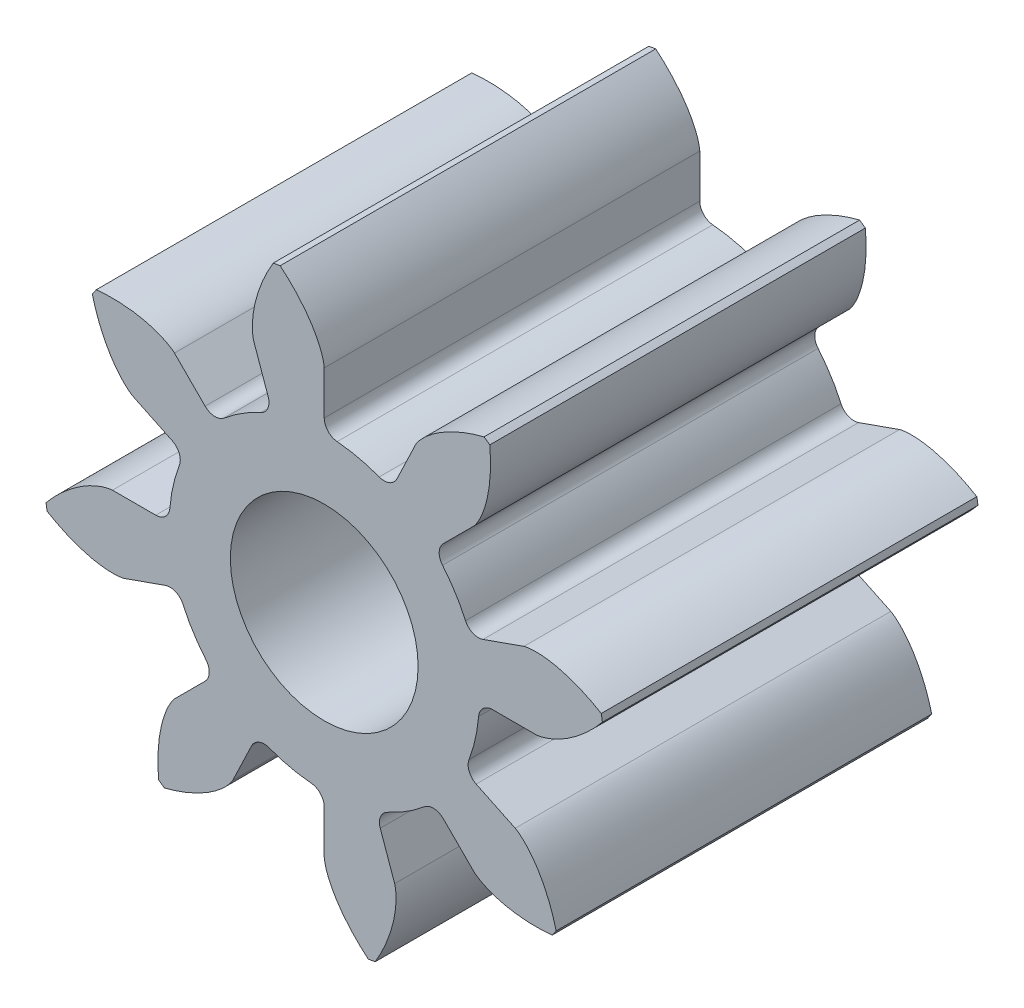
SolidWorks part; units mm, degrees
material "Laiton"
ref_plane "Front Plane" through (0, 0, 0) normal (0, 0, 1) x (1, 0, 0)
ref_plane "Top Plane" through (0, 0, 0) normal (0, 1, 0) x (1, 0, 0)
ref_plane "Right Plane" through (0, 0, 0) normal (1, 0, 0) x (0, 0, -1)
sketch "Sketch1" plane through (0, 0, 0) normal (0, 0, 1) x (1, 0, 0)
  line L0 (1.1276, 0) -> (0.825, 0)
  line L1 (1.4785, 0.2532) -> (-1.4785, -0.2532)
  line L2 (0, 0) -> (1.1999, 0.0179) construction
  circle A0 centre (0, 0) radius 1.1276 construction
  circle A1 centre (0, 0) radius 1.5
  circle A2 centre (0, 0) radius 0.825
  circle A3 centre (0, 0) radius 1.2 construction
  spline S0 degree 4 poles (1.1276, 0) (1.1285, 0) (1.1308, 0.0001) (1.1352, 0.0005) (1.1424, 0.0015) (1.1514, 0.0032) (1.1631, 0.0059) (1.1767, 0.0097) (1.1914, 0.0146) (1.2073, 0.0206) (1.2229, 0.0273) (1.2383, 0.0345) (1.2534, 0.0422) (1.2714, 0.0521) (1.2927, 0.0649) (1.3171, 0.0809) (1.3439, 0.1005) (1.3705, 0.1219) (1.3959, 0.1441) (1.4206, 0.1679) (1.444, 0.1917) (1.4673, 0.2177) (1.4883, 0.2424) (1.5106, 0.2713) (1.5284, 0.295) (1.5505, 0.3276) (1.5632, 0.3473) (1.5775, 0.3707) (1.5837, 0.3813) (1.5875, 0.3879) knots 0 0 0 0 0 0.005377 0.015084 0.028532 0.04661 0.064855 0.092111 0.119476 0.146842 0.174209 0.201575 0.228941 0.256307 0.307035 0.361767 0.4165 0.471232 0.525964 0.580697 0.635429 0.690161 0.744894 0.799626 0.854358 0.909091 0.954545 1 1 1 1 1 construction
  spline S1 degree 4 poles (1.1276, 0) (1.1285, 0) (1.1308, 0.0001) (1.1352, 0.0005) (1.1424, 0.0015) (1.1514, 0.0032) (1.1631, 0.0059) (1.1767, 0.0097) (1.1914, 0.0146) (1.2073, 0.0206) (1.2229, 0.0273) (1.2383, 0.0345) (1.2534, 0.0422) (1.2714, 0.0521) (1.2927, 0.0649) (1.3171, 0.0809) (1.3439, 0.1005) (1.3705, 0.1219) (1.3959, 0.1441) (1.4206, 0.1679) (1.444, 0.1917) (1.4673, 0.2177) (1.4883, 0.2424) (1.5106, 0.2713) (1.5284, 0.295) (1.5457, 0.3205) (1.554, 0.3331) (1.5581, 0.3396) knots 0 0 0 0 0 0.005377 0.015084 0.028532 0.04661 0.064855 0.092111 0.119476 0.146842 0.174209 0.201575 0.228941 0.256307 0.307035 0.361767 0.4165 0.471232 0.525964 0.580697 0.635429 0.690161 0.744894 0.799626 0.854358 0.909091 0.909091 0.909091 0.909091 0.909091
  dimension "D1" = 2.2553
  dimension "D2" = 3
  dimension "D3" = 1.65
  dimension "D5" = 2.4
  dimension "D4" = 8.863
extrude "Boss-Extrude3" add sketch "Sketch1" along normal blind 2 contours L1 A2 | A2 L1 | L0 S1 A1 L1 A2
mirror "Mirror2" about plane through (0, 0, 2) normal (0.1688, -0.9857, 0) of "Boss-Extrude3"
fillet "Fillet1" radius 0.075 2 edges at (0.778, 0.2745, 1) (0.825, 0, 1)
pattern_circular "CirPattern8" count 8 over 360 about axis through (0, 0, 2) along (0, 0, -1) of "Boss-Extrude3", "Mirror2", "Fillet1"
sketch "Sketch3" plane through (0, 0, 2) normal (0, 0, 1) x (1, 0, 0)
  circle A0 centre (0, 0) radius 0.5
  dimension "D1" = 1
extrude "Cut-Extrude2" cut sketch "Sketch3" against normal through all
equation "\"d\"= \"m\" * \"N\"'Pitch diameter"
equation "\"N\"= 8'Number of teeth"
equation "\"bl\"= 0.1mm'Backlash"
equation "\"pa\"= 20deg'Pressure angle (deg)"
equation "\"pc\"= ( 3.1415 * \"d\" ) / \"N\"\t'Circular pitch"
equation "\"m\"= 0.3'module"
equation "\"P\"= \"N\" / \"d\"\t\t\t'Diametral pitch"
equation "\"a\"= 1/\"P\"\t\t\t'Addendum distance"
equation "\"b\"= 1.25 / \"P\"'Dedendum distance"
equation "\"rb\"= (\"d\"/2)*cos(\"pa\")\t\t'base circle radius"
equation "\"cp\"= 3.1415/\"P\"\t\t'Circular pitch"
equation "\"t\"= ( \"cp\" / 2 ) - \"bl\"'tooth tickness"
equation "\"c\"=\"b\"-\"a\"\t\t\t'Clearance"
equation "\"facewidth\"= 2mm'face width"
equation "\"rbd\"= \"rb\" * 2'base circle diameter"
equation "\"D1@Sketch1\"=\"rbd\""
equation "\"D2@Sketch1\"= \"d\" + (\"a\" * 2)"
equation "\"D3@Sketch1\" = \"ded\""
equation "\"D4@Sketch1\"= ((\"t\" /2) / (\"d\"/2)) * (180/3.1415)"
equation "\"D1@Boss-Extrude3\"=\"facewidth\""
equation "\"D1@Fillet1\"=\"c\""
equation "\"D1@CirPattern8\"=\"N\""
equation "\"D5@Sketch1\"=\"d\""
equation "\"ded1\"= \"d\" - 2 * ( ( ( \"d\" / 2 ) - \"rb\" ) + ( 0.5 * ( 1.25 / \"P\" ) ) )"
equation "\"ded2\"= \"d\" - ( \"b\" * 2 )"
equation "\"ded\"= IIF ( \"rb\" < ( \"ded2\" / 2 ) , \"ded1\" , \"ded2\" )"
equation "\"shaftdia\"= 1mm"
equation "\"D1@Sketch3\"=\"shaftdia\""
